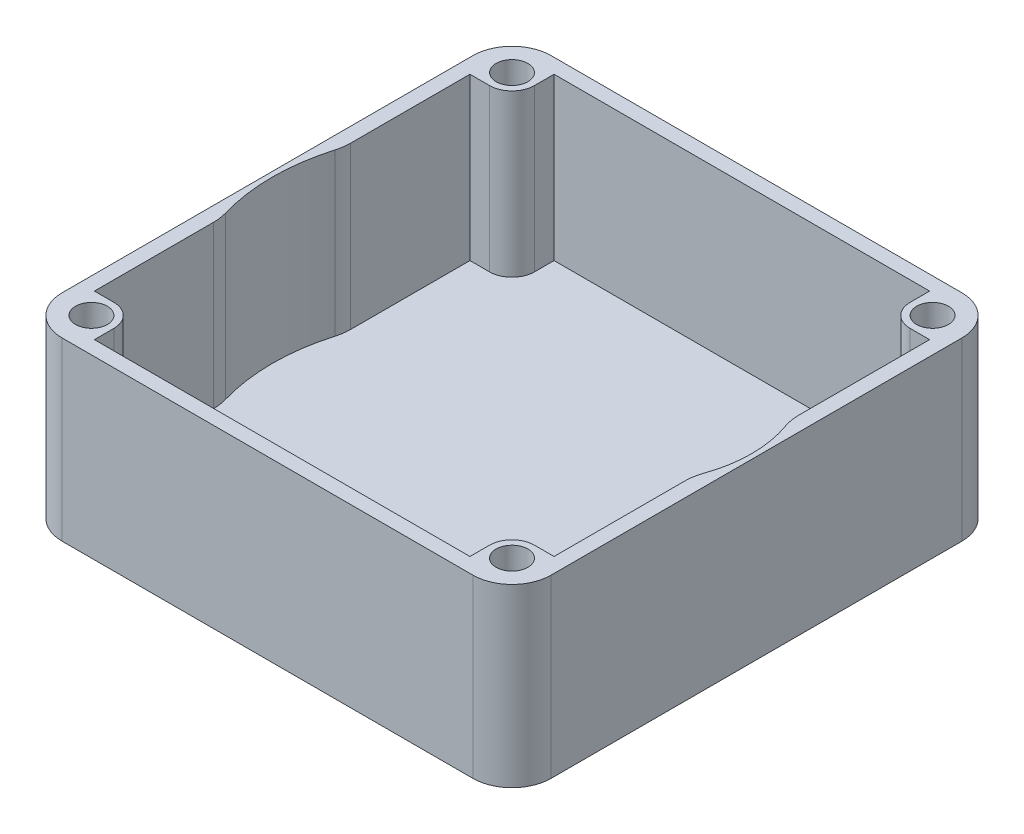
SolidWorks part; units mm, degrees
ref_plane "Спереди" through (0, 0, 0) normal (0, 0, 1) x (1, 0, 0)
ref_plane "Сверху" through (0, 0, 0) normal (0, 1, 0) x (1, 0, 0)
ref_plane "Справа" through (0, 0, 0) normal (1, 0, 0) x (0, 0, -1)
sketch "Эскиз1" plane through (0, 0, 0) normal (0, 1, 0) x (1, 0, 0)
  line L0 (0, 50) -> (100, 50) construction
  line L17 (0, 0) -> (100, 0)
  line L18 (0, 0) -> (0, 100)
  line L19 (0, 100) -> (100, 100)
  line L20 (100, 0) -> (100, 100)
  line L21 (50, 100) -> (50, 0) construction
  dimension "D1" = 100
  dimension "D2" = 100
extrude "Бобышка-Вытянуть1" add sketch "Эскиз1" along normal blind 3
sketch "Эскиз4" plane through (0, 3, 0) normal (0, 1, 0) x (1, 0, 0)
  line L0 (97, 97) -> (3, 97)
  line L1 (3, 97) -> (3, 64)
  line L2 (3, 3) -> (97, 3)
  line L3 (97, 3) -> (97, 38.3381)
  line L4 (0, 100) -> (0, 0)
  line L5 (0, 0) -> (100, 0)
  line L6 (100, 0) -> (100, 100)
  line L7 (100, 100) -> (0, 100)
  line L8 (0, 100) -> (0, 0)
  line L9 (0, 0) -> (100, 0)
  line L10 (100, 0) -> (100, 100)
  line L11 (100, 100) -> (0, 100)
  line L12 (0, 50) -> (100, 50) construction
  line L13 (3, 36) -> (3, 3)
  line L14 (3, 97) -> (3, 3) construction
  line L15 (97, 61.6619) -> (97, 97)
  line L16 (97, 3) -> (97, 97) construction
  arc A0 (2.6, 61.2) -> (2.6, 38.8) centre (41, 50) ccw
  arc A1 (97.5714, 41.6701) -> (97.5714, 58.3299) centre (74, 50) ccw
  arc A2 (97.5714, 58.3299) -> (97, 61.6619) centre (107, 61.6619) cw
  arc A3 (97.5714, 41.6701) -> (97, 38.3381) centre (107, 38.3381) ccw
  arc A4 (2.6, 38.8) -> (3, 36) centre (-7, 36) cw
  arc A5 (2.6, 61.2) -> (3, 64) centre (-7, 64) ccw
  point P12 (1, 50)
  point P16 (99, 50)
  point P20 (97, 59.798)
  point P25 (3, 37.51)
  dimension "D4" = 80
  dimension "D6" = 50
  dimension "D7" = 10
  dimension "D3" = 1
  dimension "D5" = 1
  dimension "D1" = 0
  dimension "D2" = 3
extrude "Бобышка-Вытянуть4" add sketch "Эскиз4" along normal blind 33
fillet "Скругление3" radius 8 4 edges at (100, 18, -100) (100, 18, 0) (0, 18, 0) (0, 18, -100)
sketch "Эскиз7" plane through (0, 3, 0) normal (0, 1, 0) x (1, 0, 0)
  line L0 (3, 97) -> (3, 64) construction
  line L2 (97, 97) -> (3, 97) construction
  line L6 (50, 97) -> (50, 3) construction
  line L7 (3, 3) -> (97, 3) construction
  line L8 (0, 50) -> (100, 50) construction
  line L9 (0, 92) -> (0, 8) construction
  line L10 (100, 8) -> (100, 92) construction
  line L15 (3, 89) -> (3, 97) construction
  line L16 (3, 97) -> (11, 97) construction
  line L17 (7, 89) -> (3, 89) construction
  line L18 (3, 97) -> (3, 64) construction
  line L19 (11, 93) -> (11, 97) construction
  line L20 (97, 97) -> (3, 97) construction
  line L21 (89, 93) -> (89, 97) construction
  line L22 (93, 89) -> (97, 89) construction
  line L23 (97, 97) -> (89, 97) construction
  line L24 (97, 89) -> (97, 97) construction
  line L25 (97, 11) -> (97, 3) construction
  line L26 (97, 3) -> (89, 3) construction
  line L27 (93, 11) -> (97, 11) construction
  line L28 (89, 7) -> (89, 3) construction
  line L29 (11, 7) -> (11, 3) construction
  line L30 (7, 11) -> (3, 11) construction
  line L31 (3, 3) -> (11, 3) construction
  line L32 (3, 11) -> (3, 3) construction
  line L33 (7, 88.4) -> (2.4, 88.4)
  line L34 (2.4, 88.4) -> (2.4, 97.6)
  line L35 (2.4, 97.6) -> (11.6, 97.6)
  line L36 (11.6, 93) -> (11.6, 97.6)
  line L37 (93, 88.4) -> (97.6, 88.4)
  line L38 (97.6, 88.4) -> (97.6, 97.6)
  line L39 (97.6, 97.6) -> (88.4, 97.6)
  line L40 (88.4, 93) -> (88.4, 97.6)
  line L41 (88.4, 7) -> (88.4, 2.4)
  line L42 (97.6, 2.4) -> (88.4, 2.4)
  line L43 (97.6, 11.6) -> (97.6, 2.4)
  line L44 (93, 11.6) -> (97.6, 11.6)
  line L45 (11.6, 7) -> (11.6, 2.4)
  line L46 (2.4, 2.4) -> (11.6, 2.4)
  line L47 (2.4, 11.6) -> (2.4, 2.4)
  line L48 (7, 11.6) -> (2.4, 11.6)
  arc A0 (7, 89) -> (11, 93) centre (7, 93) ccw construction
  arc A2 (7, 88.4) -> (11.6, 93) centre (7, 93) ccw
  arc A3 (93, 88.4) -> (88.4, 93) centre (93, 93) cw
  arc A4 (93, 11.6) -> (88.4, 7) centre (93, 7) ccw
  arc A5 (7, 11.6) -> (11.6, 7) centre (7, 7) cw
  circle A18 centre (7, 93) radius 3.25
  circle A19 centre (93, 93) radius 3.25
  arc A20 (93, 89) -> (89, 93) centre (93, 93) cw construction
  arc A21 (93, 11) -> (89, 7) centre (93, 7) ccw construction
  circle A22 centre (93, 7) radius 3.25
  circle A23 centre (7, 7) radius 3.25
  arc A24 (7, 11) -> (11, 7) centre (7, 7) cw construction
  dimension "D1" = 6.5
  dimension "D2" = 0.6
  dimension "D3" = 0.6
  dimension "D4" = 0.6
  dimension "D5" = 0.6
extrude "Бобышка-Вытянуть6" add sketch "Эскиз7" along normal up to surface (33 mm away) up to face at (50, 36, -50)
